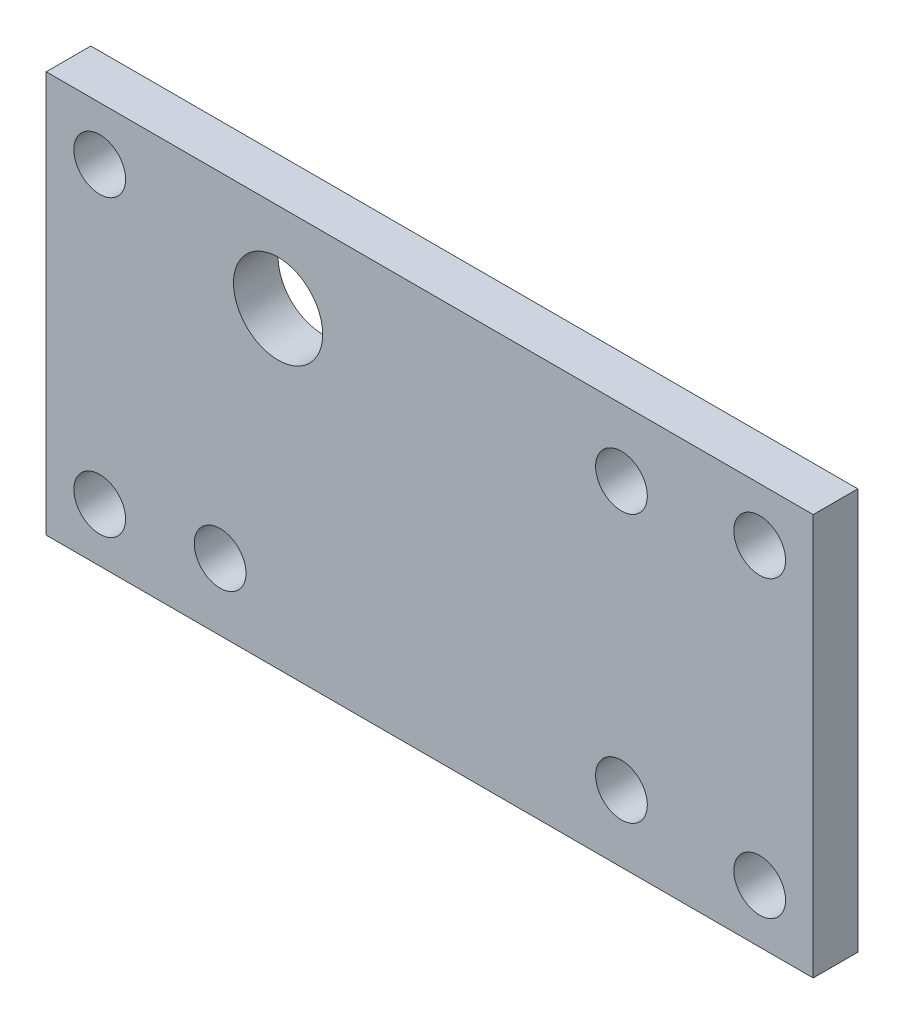
SolidWorks part; units mm, degrees
ref_plane "Front Plane" through (0, 0, 0) normal (0, 0, 1) x (1, 0, 0)
ref_plane "Top Plane" through (0, 0, 0) normal (0, 1, 0) x (1, 0, 0)
ref_plane "Right Plane" through (0, 0, 0) normal (1, 0, 0) x (0, 0, -1)
sketch "Sketch1" plane through (0, 0, 0) normal (0, 0, 1) x (1, 0, 0)
  line L1 (-27.305, 14.2875) -> (27.305, 14.2875)
  line L2 (-27.305, 14.2875) -> (-27.305, -14.2875)
  line L3 (-27.305, -14.2875) -> (27.305, -14.2875)
  line L4 (27.305, 14.2875) -> (27.305, -14.2875)
  line L5 (-27.305, 14.2875) -> (27.305, -14.2875) construction
  line L6 (-27.305, -14.2875) -> (27.305, 14.2875) construction
  circle A0 centre (-10.795, 7.9375) radius 3.175
  point P0 (0, 0)
  dimension "D4" = 6.35
  dimension "D1" = 28.575
  dimension "D2" = 54.61
  dimension "D3" = 6.35
  dimension "D5" = 38.1
extrude "Boss-Extrude1" add sketch "Sketch1" along normal blind 3.175
sketch "Sketch2" plane through (0, 0, 3.175) normal (0, 0, 1) x (1, 0, 0)
  line L0 (-27.305, 14.2875) -> (-27.305, -14.2875) construction
  line L1 (27.305, 14.2875) -> (-27.305, 14.2875) construction
  line L2 (-27.305, -14.2875) -> (27.305, -14.2875) construction
  line L3 (27.305, -14.2875) -> (27.305, 14.2875) construction
  circle A0 centre (-23.495, 10.4775) radius 1.8415
  circle A1 centre (-23.495, -10.4775) radius 1.8415
  circle A2 centre (23.495, -10.4775) radius 1.8415
  circle A3 centre (23.495, 10.4775) radius 1.8415
  dimension "D3" = 3.683
  dimension "D1" = 3.81
  dimension "D2" = 3.81
  dimension "D4" = 3.81
  dimension "D5" = 3.81
extrude "Cut-Extrude1" cut sketch "Sketch2" against normal through all
sketch "Sketch4" plane through (0, 0, 3.175) normal (0, 0, 1) x (1, 0, 0)
  line L0 (27.305, 14.2875) -> (-27.305, 14.2875) construction
  line L1 (27.305, -14.2875) -> (27.305, 14.2875) construction
  circle A0 centre (13.6525, 9.525) radius 1.8415
  dimension "D3" = 3.683
  dimension "D1" = 4.7625
  dimension "D2" = 13.6525
extrude "Cut-Extrude2" cut sketch "Sketch4" against normal through all
sketch "Sketch5" plane through (0, 0, 3.175) normal (0, 0, 1) x (1, 0, 0)
  line L0 (27.305, -14.2875) -> (27.305, 14.2875) construction
  line L1 (-27.305, -14.2875) -> (27.305, -14.2875) construction
  circle A0 centre (-14.9225, -9.525) radius 1.8415
  circle A1 centre (13.6525, -9.525) radius 1.8415
  point P6 (0, 0)
  point P9 (13.6525, -9.525)
  dimension "D3" = 3.683
  dimension "D1" = 13.6525
  dimension "D2" = 28.575
  dimension "D4" = 4.7625
extrude "Cut-Extrude3" cut sketch "Sketch5" against normal through all
